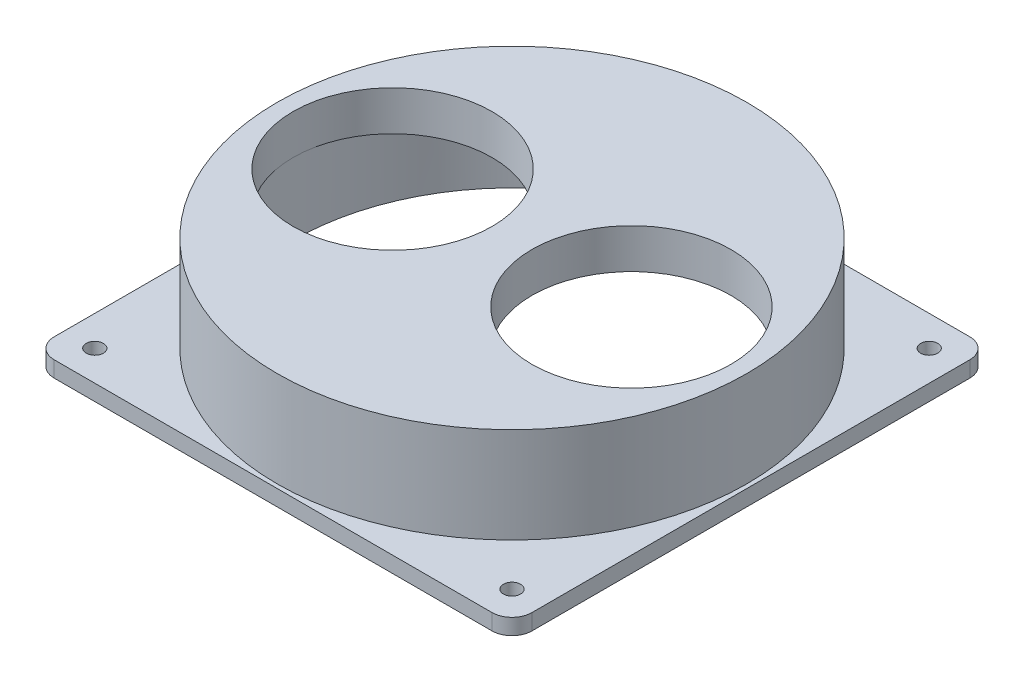
SolidWorks part; units mm, degrees
ref_plane "Front Plane" through (0, 0, 0) normal (0, 0, 1) x (1, 0, 0)
ref_plane "Top Plane" through (0, 0, 0) normal (0, 1, 0) x (1, 0, 0)
ref_plane "Right Plane" through (0, 0, 0) normal (1, 0, 0) x (0, 0, -1)
sketch "Sketch1" plane through (0, 0, 0) normal (0, 1, 0) x (1, 0, 0)
  line L1 (-60, 60) -> (60, 60)
  line L2 (-60, 60) -> (-60, -60)
  line L3 (-60, -60) -> (60, -60)
  line L4 (60, 60) -> (60, -60)
  line L5 (-60, 60) -> (60, -60) construction
  line L6 (-60, -60) -> (60, 60) construction
  point P0 (0, 0)
  dimension "D1" = 120
  dimension "D2" = 120
extrude "Boss-Extrude1" add sketch "Sketch1" along normal blind 4
fillet "Fillet1" radius 5 4 edges at (60, 2, -60) (-60, 2, -60) (-60, 2, 60) (60, 2, 60)
sketch "Sketch2" plane through (0, 4, 0) normal (0, 1, 0) x (1, 0, 0)
  line L0 (55, 60) -> (-55, 60) construction
  line L1 (-60, 55) -> (-60, -55) construction
  line L2 (60, -55) -> (60, 55) construction
  line L3 (-55, -60) -> (55, -60) construction
  circle A0 centre (-52.4, 52.4) radius 2.15
  circle A1 centre (52.4, 52.4) radius 2.15
  circle A2 centre (-52.4, -52.4) radius 2.15
  circle A3 centre (52.4, -52.4) radius 2.15
  dimension "D1" = 4.3
  dimension "D2" = 7.6
  dimension "D3" = 7.6
  dimension "D4" = 4.3
  dimension "D5" = 7.6
  dimension "D6" = 7.6
  dimension "D7" = 4.3
  dimension "D8" = 7.6
  dimension "D9" = 7.6
  dimension "D10" = 4.3
  dimension "D11" = 7.6
  dimension "D12" = 7.6
extrude "Cut-Extrude1" cut sketch "Sketch2" against normal blind 4
sketch "Sketch3" plane through (0, 4, 0) normal (0, 1, 0) x (1, 0, 0)
  circle A0 centre (0, 0) radius 55
  dimension "D1" = 110
extrude "Cut-Extrude2" cut sketch "Sketch3" against normal blind 4
sketch "Sketch5" plane through (0, 4, 0) normal (0, 1, 0) x (1, 0, 0)
  circle A0 centre (0, 0) radius 59
  circle A1 centre (0, 0) radius 55 construction
  circle A2 centre (0, 0) radius 55
  dimension "D1" = 4
extrude "Boss-Extrude2" add sketch "Sketch5" along normal blind 20
sketch "Sketch6" plane through (0, 24, 0) normal (0, 1, 0) x (1, 0, 0)
  circle A0 centre (0, 0) radius 59
extrude "Boss-Extrude3" add sketch "Sketch6" along normal blind 4
sketch "Sketch7" plane through (0, 28, 0) normal (0, 1, 0) x (1, 0, 0)
  circle A0 centre (30, 0) radius 25
  circle A1 centre (-30, 0) radius 25
  dimension "D3" = 50
  dimension "D4" = 50
  dimension "D1" = 30
  dimension "D2" = 30
extrude "Cut-Extrude3" cut sketch "Sketch7" against normal blind 4
sketch "Sketch8" plane through (0, 24, 0) normal (0, -1, 0) x (1, 0, 0)
  circle A0 centre (30, 0) radius 29
  circle A1 centre (-30, 0) radius 29
  circle A2 centre (30, 0) radius 25 construction
  circle A3 centre (-30, 0) radius 25 construction
  circle A4 centre (30, 0) radius 25
  circle A5 centre (-30, 0) radius 25
  dimension "D1" = 4
  dimension "D2" = 4
extrude "Boss-Extrude4" add sketch "Sketch8" along normal blind 6
